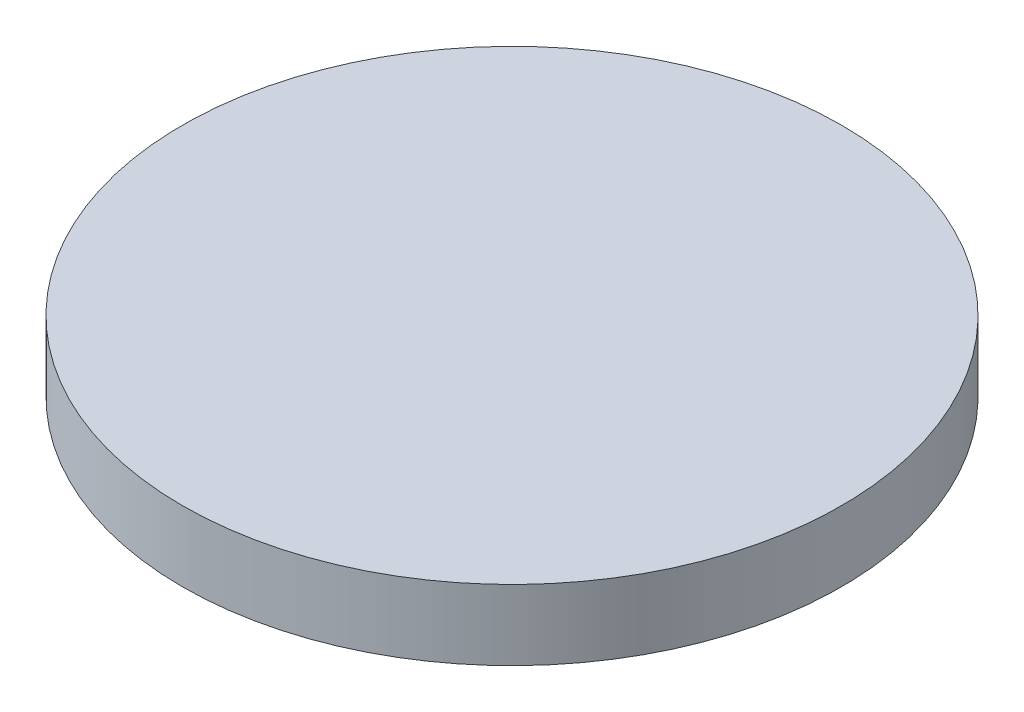
SolidWorks part; units mm, degrees
ref_plane "Front" through (0, 0, 0) normal (0, 0, 1) x (1, 0, 0)
ref_plane "Top" through (0, 0, 0) normal (0, 1, 0) x (1, 0, 0)
ref_plane "Right" through (0, 0, 0) normal (1, 0, 0) x (0, 0, -1)
sketch "Çizim1" plane through (0, 0, 0) normal (0, 1, 0) x (1, 0, 0)
  circle A0 centre (-10.5923, -2.1804) radius 15
  dimension "D1" = 30
extrude "Yükseklik-Ekstrüzyon1" add sketch "Çizim1" along normal blind 3.2
